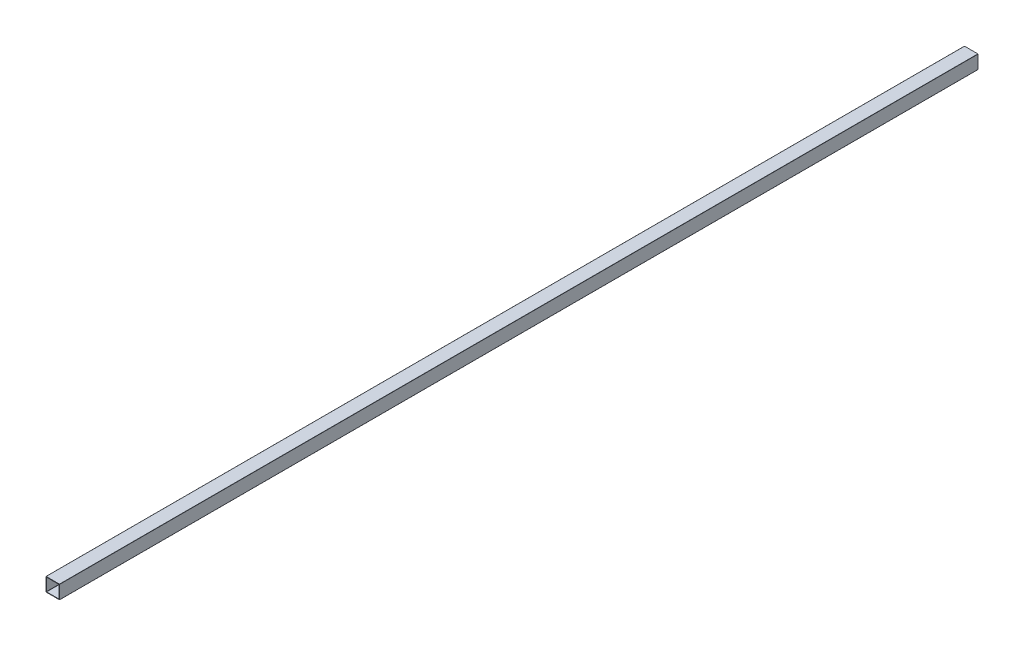
SolidWorks part; units mm, degrees
material "AISI 1035 Acero (SS)"
ref_plane "Alzado" through (0, 0, 0) normal (0, 0, 1) x (1, 0, 0)
ref_plane "Planta" through (0, 0, 0) normal (0, 1, 0) x (1, 0, 0)
ref_plane "Vista lateral" through (0, 0, 0) normal (1, 0, 0) x (0, 0, -1)
sketch "Croquis1" plane through (0, 0, 0) normal (0, 0, 1) x (1, 0, 0)
  line L0 (-41.41, -41.41) -> (-41.41, 41.41)
  line L1 (-44.45, -44.45) -> (44.45, -44.45)
  line L2 (-44.45, -44.45) -> (-44.45, 44.45)
  line L3 (-44.45, 44.45) -> (44.45, 44.45)
  line L4 (44.45, -44.45) -> (44.45, 44.45)
  line L5 (-44.45, -44.45) -> (44.45, 44.45) construction
  line L6 (-44.45, 44.45) -> (44.45, -44.45) construction
  line L7 (-41.41, 41.41) -> (41.41, 41.41)
  line L8 (41.41, -41.41) -> (41.41, 41.41)
  line L9 (-41.41, -41.41) -> (41.41, -41.41)
  point P0 (0, 0)
  dimension "D1" = 88.9
  dimension "D3" = 3.04
extrude "Saliente-Extruir1" add sketch "Croquis1" against normal blind 6000
fillet "Redondeo1" radius 1 8 edges at (-41.41, 41.41, -3000) (41.41, 41.41, -3000) (41.41, -41.41, -3000) (-44.45, -44.45, -3000) (-44.45, 44.45, -3000) (-41.41, -41.41, -3000) (44.45, -44.45, -3000) (44.45, 44.45, -3000)
